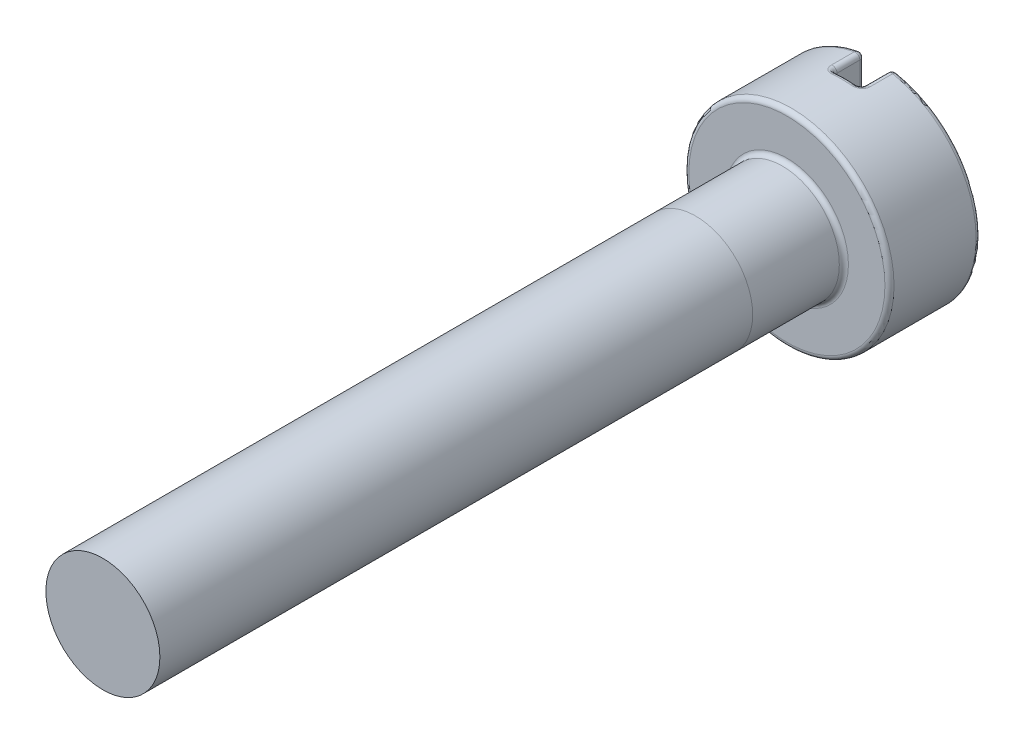
SolidWorks part; units mm, degrees
ref_plane "Front Plane" through (0, 0, 0) normal (0, 0, 1) x (1, 0, 0)
ref_plane "Top Plane" through (0, 0, 0) normal (0, 1, 0) x (1, 0, 0)
ref_plane "Right Plane" through (0, 0, 0) normal (1, 0, 0) x (0, 0, -1)
sketch "Sketch1" plane through (0, 0, 0) normal (0, 0, 1) x (1, 0, 0)
  circle A0 centre (0, 0) radius 0.625
  dimension "D1" = 1.25
extrude "Boss-Extrude1" add sketch "Sketch1" along normal blind 7.5
sketch "Sketch2" plane through (0, 0, 0) normal (0, 0, 1) x (1, 0, 0)
  circle A2 centre (0, 0) radius 1.125
  circle A3 centre (0, 0) radius 1.125
  dimension "D1" = 0.5
extrude "Boss-Extrude2" add sketch "Sketch2" against normal blind 1
sketch "Sketch3" plane through (0, 0, -1) normal (0, 0, -1) x (-1, 0, 0)
  line L1 (0.15, -6.7813) -> (-0.15, -6.7813)
  line L2 (0.15, -6.7813) -> (0.15, 6.7813)
  line L3 (0.15, 6.7813) -> (-0.15, 6.7813)
  line L4 (-0.15, -6.7813) -> (-0.15, 6.7813)
  line L5 (0.15, -6.7813) -> (-0.15, 6.7813) construction
  line L6 (0.15, 6.7813) -> (-0.15, -6.7813) construction
  point P0 (0, 0)
  dimension "D1" = 0.3
extrude "Cut-Extrude1" cut sketch "Sketch3" against normal blind 0.35
fillet "Fillet1" radius 0.05 12 edges at (-0.15, -1.115, -0.825) (-0.15, 1.115, -0.825) (0.15, 1.115, -0.825) (0.15, -1.115, -0.825) (0, 1.125, -0.65) (0, -1.125, -0.65) (0.15, 0, -0.65) (-0.15, 0, -0.65) (-0.15, 0, -1) (-1.125, 0, -1) (0.15, 0, -1) (1.125, 0, -1)
fillet "Fillet2" radius 0.05 2 edges at (1.125, 0, 0) (0.625, 0, 0)
sketch "Sketch4" plane through (0, 0, 0) normal (1, 0, 0) x (0, 0, -1)
  line L0 (-1, -3.6683) -> (-1, 4.4314)
  line L1 (-7.5, 0.625) -> (-7.5, -0.625) construction
  dimension "D1" = 6.5
split line "Split Line1"
